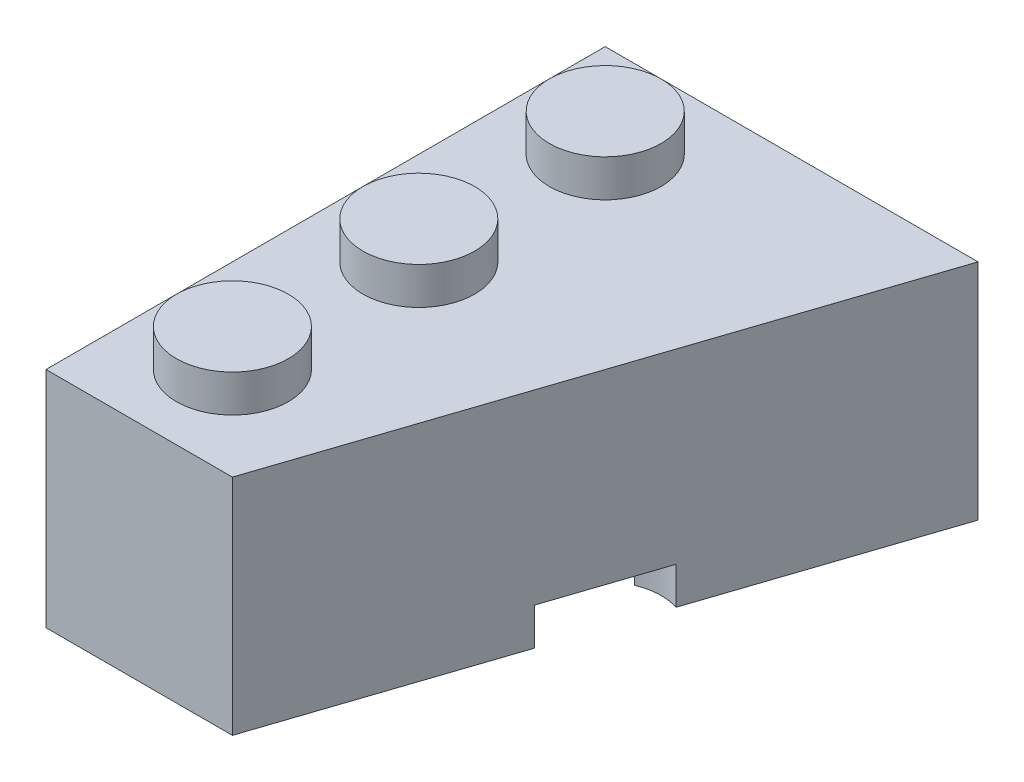
SolidWorks part; units mm, degrees
ref_plane "Front Plane" through (0, 0, 0) normal (0, 0, 1) x (1, 0, 0)
ref_plane "Top Plane" through (0, 0, 0) normal (0, 1, 0) x (1, 0, 0)
ref_plane "Right Plane" through (0, 0, 0) normal (1, 0, 0) x (0, 0, -1)
sketch "Sketch1" plane through (0, 0, 0) normal (0, 1, 0) x (1, 0, 0)
  line L0 (0, 0) -> (8, 0)
  line L1 (8, 0) -> (16, 24)
  line L2 (16, 24) -> (0, 24)
  line L3 (0, 24) -> (0, 0)
  dimension "D1" = 8
  dimension "D2" = 24
  dimension "D3" = 16
extrude "Boss-Extrude1" add sketch "Sketch1" along normal blind 9.6
sketch "Sketch2" plane through (0, 9.6, 0) normal (0, 1, 0) x (1, 0, 0)
  line L0 (0, 0) -> (4, 0) construction
  line L1 (0, 0) -> (8, 0) construction
  line L2 (4, 0) -> (4, 4) construction
  circle A0 centre (4, 4) radius 2.4
  dimension "D2" = 4.8
  dimension "D1" = 4
extrude "Boss-Extrude2" add sketch "Sketch2" along normal blind 1.6
pattern_linear "LPattern1" count 3 spacing 8 along (0, 0, -1) of "Boss-Extrude2"
shell "Shell1" thickness 1.6
sketch "Sketch3" plane through (0, 0, 0) normal (0, -1, 0) x (1, 0, 0)
  line L0 (16, -24) -> (12, -24) construction
  line L5 (12, -24) -> (12, -20) construction
  line L6 (12, -20) -> (12, -12) construction
  line L7 (16, -24) -> (0, -24) construction
  circle A0 centre (12, -20) radius 2.4
  circle A1 centre (12, -12) radius 2.4
  point P0 (0, 0)
  dimension "D3" = 4.8
  dimension "D4" = 4.8
  dimension "D1" = 4
  dimension "D2" = 8
  dimension "D5" = 4
extrude "Cut-Extrude1" cut sketch "Sketch3" against normal blind 1.6 contours A1 | A0
